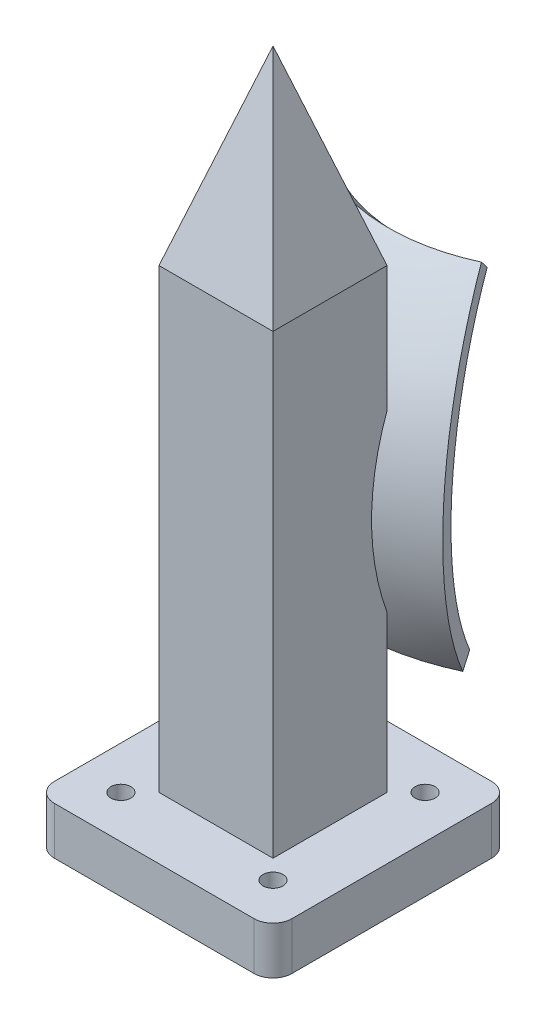
SolidWorks part; units mm, degrees
material "ABS PC"
ref_plane "Front Plane" through (0, 0, 0) normal (0, 0, 1) x (1, 0, 0)
ref_plane "Top Plane" through (0, 0, 0) normal (0, 1, 0) x (1, 0, 0)
ref_plane "Right Plane" through (0, 0, 0) normal (1, 0, 0) x (0, 0, -1)
sketch "Sketch1" plane through (0, 0, 0) normal (0, 1, 0) x (1, 0, 0)
  line L1 (0, 0) -> (25, 0)
  line L2 (0, 0) -> (0, 25)
  line L3 (0, 25) -> (25, 25)
  line L4 (25, 0) -> (25, 25)
  dimension "D1" = 25
  dimension "D2" = 25
extrude "Boss-Extrude1" add sketch "Sketch1" along normal blind 5
sketch "Sketch2" plane through (0, 5, 0) normal (0, 1, 0) x (1, 0, 0)
  line L0 (0, 0) -> (25, 0) construction
  line L1 (0, 25) -> (0, 0) construction
  line L2 (25, 0) -> (25, 25) construction
  line L3 (25, 25) -> (0, 25) construction
  circle A0 centre (4.5, 4.5) radius 1.05
  circle A1 centre (20.5, 4.5) radius 1.05
  circle A2 centre (20.5, 20.5) radius 1.05
  circle A3 centre (4.5, 20.5) radius 1.05
  dimension "D1" = 2.1
  dimension "D4" = 2.1
  dimension "D6" = 2.1
  dimension "D8" = 2.1
  dimension "D2" = 4.5
  dimension "D3" = 4.5
  dimension "D5" = 4.5
  dimension "D7" = 4.5
extrude "Cut-Extrude1" cut sketch "Sketch2" against normal blind 5
fillet "Fillet1" radius 2 4 edges at (0, 2.5, -25) (0, 2.5, 0) (25, 2.5, -25) (25, 2.5, 0)
sketch "Sketch3" plane through (0, 5, 0) normal (0, 1, 0) x (1, 0, 0)
  line L0 (2, 0) -> (23, 0) construction
  line L1 (6.5, 6.5) -> (18.5, 6.5)
  line L2 (6.5, 6.5) -> (6.5, 18.5)
  line L3 (6.5, 18.5) -> (18.5, 18.5)
  line L4 (18.5, 6.5) -> (18.5, 18.5)
  line L5 (25, 2) -> (25, 23) construction
  line L7 (9.5, 15.5) -> (15.5, 15.5)
  line L8 (9.5, 15.5) -> (9.5, 9.5)
  line L9 (9.5, 9.5) -> (15.5, 9.5)
  line L10 (15.5, 15.5) -> (15.5, 9.5)
  line L11 (9.5, 15.5) -> (15.5, 9.5) construction
  line L12 (9.5, 9.5) -> (15.5, 15.5) construction
  point P8 (12.5, 12.5)
  dimension "D1" = 12
  dimension "D2" = 6.5
  dimension "D3" = 6.5
  dimension "D4" = 6
extrude "Boss-Extrude2" add sketch "Sketch3" along normal blind 48
sketch "Sketch4" plane through (0, 0, 0) normal (0, -1, 0) x (-1, 0, 0)
  line L1 (-9.5, 9.5) -> (-15.5, 9.5)
  line L2 (-9.5, 9.5) -> (-9.5, 15.5)
  line L3 (-9.5, 15.5) -> (-15.5, 15.5)
  line L4 (-15.5, 9.5) -> (-15.5, 15.5)
  line L5 (-9.5, 9.5) -> (-15.5, 15.5) construction
  line L6 (-9.5, 15.5) -> (-15.5, 9.5) construction
  point P0 (-12.5, 12.5)
  dimension "D1" = 6
extrude "Cut-Extrude2" cut sketch "Sketch4" against normal blind 10
sketch "Sketch5" plane through (0, 53, 0) normal (0, 1, 0) x (1, 0, 0)
  line L0 (18.5, 6.5) -> (18.5, 18.5) construction
  line L1 (6.5, 6.5) -> (18.5, 6.5)
  line L2 (6.5, 6.5) -> (6.5, 18.5)
  line L3 (6.5, 18.5) -> (18.5, 18.5)
  line L4 (18.5, 6.5) -> (18.5, 18.5)
extrude "Boss-Extrude3" add sketch "Sketch5" along normal blind 20
sketch "Sketch6" plane through (0, 0, -6.5) normal (0, 0, 1) x (1, 0, 0)
  line L0 (12.5, 73) -> (12.5, 53)
  line L1 (6.5, 73) -> (18.5, 73) construction
  line L2 (12.5, 53) -> (18.5, 53)
  line L3 (18.5, 73) -> (18.5, 5) construction
  line L4 (18.5, 53) -> (12.5, 73)
  line L5 (18.5, 73) -> (18.5, 53)
  line L6 (12.5, 73) -> (6.5, 73)
  line L7 (6.5, 73) -> (6.5, 53)
  line L8 (6.5, 73) -> (6.5, 5) construction
  line L9 (6.5, 53) -> (12.5, 73)
  line M2 (18.5, 5) -> (18.5, 73)
  line M3 (18.5, 73) -> (6.5, 73)
  line M4 (6.5, 73) -> (6.5, 5)
  dimension "D1" = 20
extrude "Cut-Extrude3" cut sketch "Sketch6" against normal blind 20 contours L4 M2 M3 | L9 M4 M3
sketch "Sketch7" plane through (6.5, 0, 0) normal (-1, 0, 0) x (0, 0, 1)
  line L0 (-6.5, 53) -> (-12.5, 73)
  line L1 (-18.5, 73) -> (-6.5, 73) construction
  line L2 (-12.5, 73) -> (-6.5, 73)
  line L3 (-6.5, 73) -> (-6.5, 53)
  line L4 (-12.5, 73) -> (-18.5, 73)
  line L5 (-18.5, 73) -> (-18.5, 53)
  line L6 (-18.5, 53) -> (-12.5, 73)
extrude "Cut-Extrude4" cut sketch "Sketch7" against normal blind 20 contours L3 L2 L0 | L5 L6 L4
ref_plane "Plane1" through (12.5, 0, 0) normal (1, 0, 0) x (0, 0, -1)
sketch "Sketch8" plane through (12.5, 0, 0) normal (1, 0, 0) x (0, 0, -1)
  line L0 (20.5589, 15.786) -> (43.617, 30.6059)
  line L1 (43.617, 30.6059) -> (24.6276, 50.3723)
  line L2 (43.617, 54.7917) -> (43.617, -9.159)
  arc A0 (20.5589, 15.786) -> (24.6276, 50.3723) centre (43.617, 30.6059) cw
  arc A1 (22.0647, 16.7538) -> (25.8677, 49.0815) centre (43.617, 30.6059) cw
revolve "Revolve1" add sketch "Sketch8" angle 25 about L2 other way angle 25
